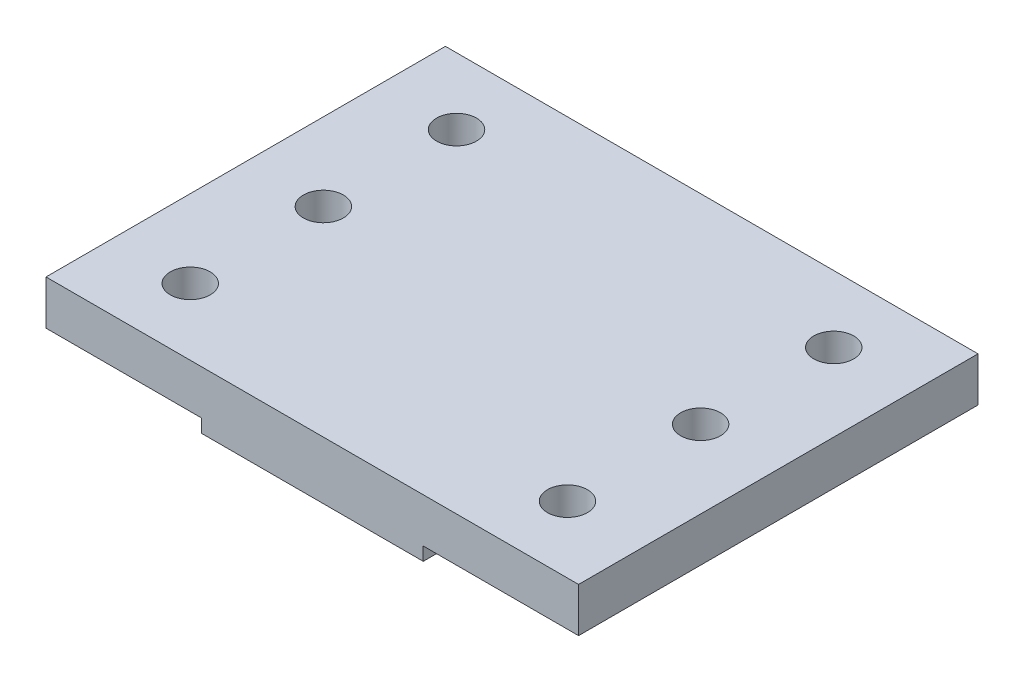
SolidWorks part; units mm, degrees
material "ABS"
ref_plane "Front Plane" through (0, 0, 0) normal (0, 0, 1) x (1, 0, 0)
ref_plane "Top Plane" through (0, 0, 0) normal (0, 1, 0) x (1, 0, 0)
ref_plane "Right Plane" through (0, 0, 0) normal (1, 0, 0) x (0, 0, -1)
sketch "Sketch1" plane through (0, 0, 0) normal (0, 0, 1) x (1, 0, 0)
  line L0 (-12.5, -2.5) -> (-12.5, -4)
  line L1 (30, 2.5) -> (-30, 2.5)
  line L2 (30, 2.5) -> (30, -2.5)
  line L3 (30, -2.5) -> (12.5, -2.5)
  line L4 (-30, 2.5) -> (-30, -2.5)
  line L5 (30, 2.5) -> (-30, -2.5) construction
  line L6 (30, -2.5) -> (-30, 2.5) construction
  line L7 (-12.5, -4) -> (12.5, -4)
  line L8 (12.5, -4) -> (12.5, -2.5)
  line L9 (-12.5, -2.5) -> (-30, -2.5)
  point P0 (0, 0)
  point P10 (-12.5, -3.25)
  dimension "D1" = 60
  dimension "D2" = 5
  dimension "D3" = 12.5
  dimension "D4" = 25
  dimension "D5" = 1.5
extrude "Boss-Extrude1" add sketch "Sketch1" along normal blind 45
sketch "Sketch2" plane through (0, 2.5, 0) normal (0, 1, 0) x (1, 0, 0)
  line L0 (-30, -22.5) -> (30, -22.5) construction
  line L1 (-30, -45) -> (-30, 0) construction
  line L2 (30, -45) -> (30, 0) construction
  line L4 (21.25, -37.5) -> (-21.25, -37.5) construction
  line L5 (21.25, -37.5) -> (21.25, -7.5) construction
  line L6 (21.25, -7.5) -> (-21.25, -7.5) construction
  line L7 (-21.25, -37.5) -> (-21.25, -7.5) construction
  line L8 (21.25, -37.5) -> (-21.25, -7.5) construction
  line L9 (21.25, -7.5) -> (-21.25, -37.5) construction
  circle A0 centre (-21.25, -7.5) radius 2.25
  circle A1 centre (-21.25, -22.5) radius 2.25
  circle A2 centre (-21.25, -37.5) radius 2.25
  circle A3 centre (21.25, -37.5) radius 2.25
  circle A4 centre (21.25, -22.5) radius 2.25
  circle A5 centre (21.25, -7.5) radius 2.25
  point P6 (0, -22.5)
  dimension "D3" = 4.5
  dimension "D4" = 4.5
  dimension "D5" = 4.5
  dimension "D6" = 4.5
  dimension "D7" = 4.5
  dimension "D8" = 4.5
  dimension "D1" = 42.5
  dimension "D2" = 30
extrude "Cut-Extrude1" cut sketch "Sketch2" against normal through all
